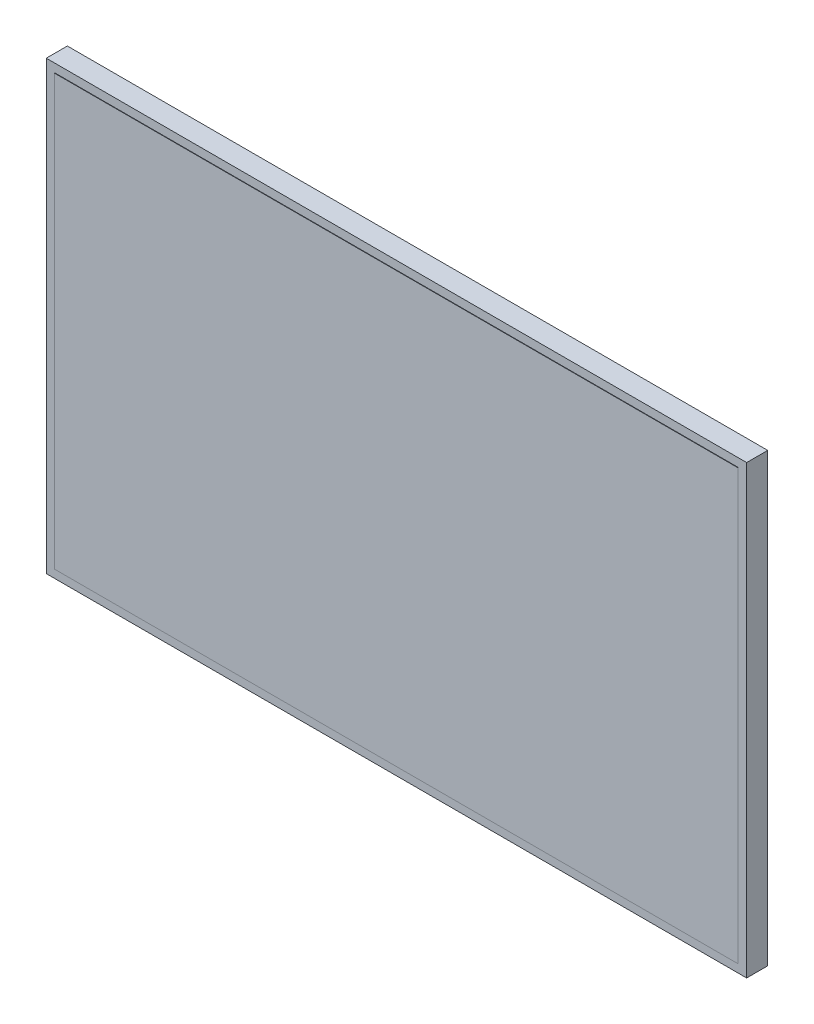
SolidWorks part; units mm, degrees
ref_plane "Alzado" through (0, 0, 0) normal (0, 0, 1) x (1, 0, 0)
ref_plane "Planta" through (0, 0, 0) normal (0, 1, 0) x (1, 0, 0)
ref_plane "Vista lateral" through (0, 0, 0) normal (1, 0, 0) x (0, 0, -1)
sketch "Croquis1" plane through (0, 0, 0) normal (0, 0, 1) x (1, 0, 0)
  line L1 (-83, -52.9) -> (83, -52.9)
  line L2 (-83, -52.9) -> (-83, 52.9)
  line L3 (-83, 52.9) -> (83, 52.9)
  line L4 (83, -52.9) -> (83, 52.9)
  line L5 (-83, -52.9) -> (83, 52.9) construction
  line L6 (-83, 52.9) -> (83, -52.9) construction
  point P0 (0, 0)
  dimension "D1" = 166
  dimension "D2" = 105.8
extrude "Saliente-Extruir1" add sketch "Croquis1" along normal mid plane 5
sketch "Croquis3" plane through (0, 0, 2.5) normal (0, 0, 1) x (1, 0, 0)
  line L0 (83, 52.9) -> (-83, 52.9) construction
  line L1 (-81, -50.9) -> (81, -50.9)
  line L2 (-81, -50.9) -> (-81, 50.9)
  line L3 (-81, 50.9) -> (81, 50.9)
  line L4 (81, -50.9) -> (81, 50.9)
  line L5 (-81, -50.9) -> (81, 50.9) construction
  line L6 (-81, 50.9) -> (81, -50.9) construction
  line L7 (-83, 52.9) -> (-83, -52.9) construction
  point P0 (0, 0)
  dimension "D1" = 2
  dimension "D2" = 2
extrude "Saliente-Extruir2" add sketch "Croquis3" along normal blind 0.1
